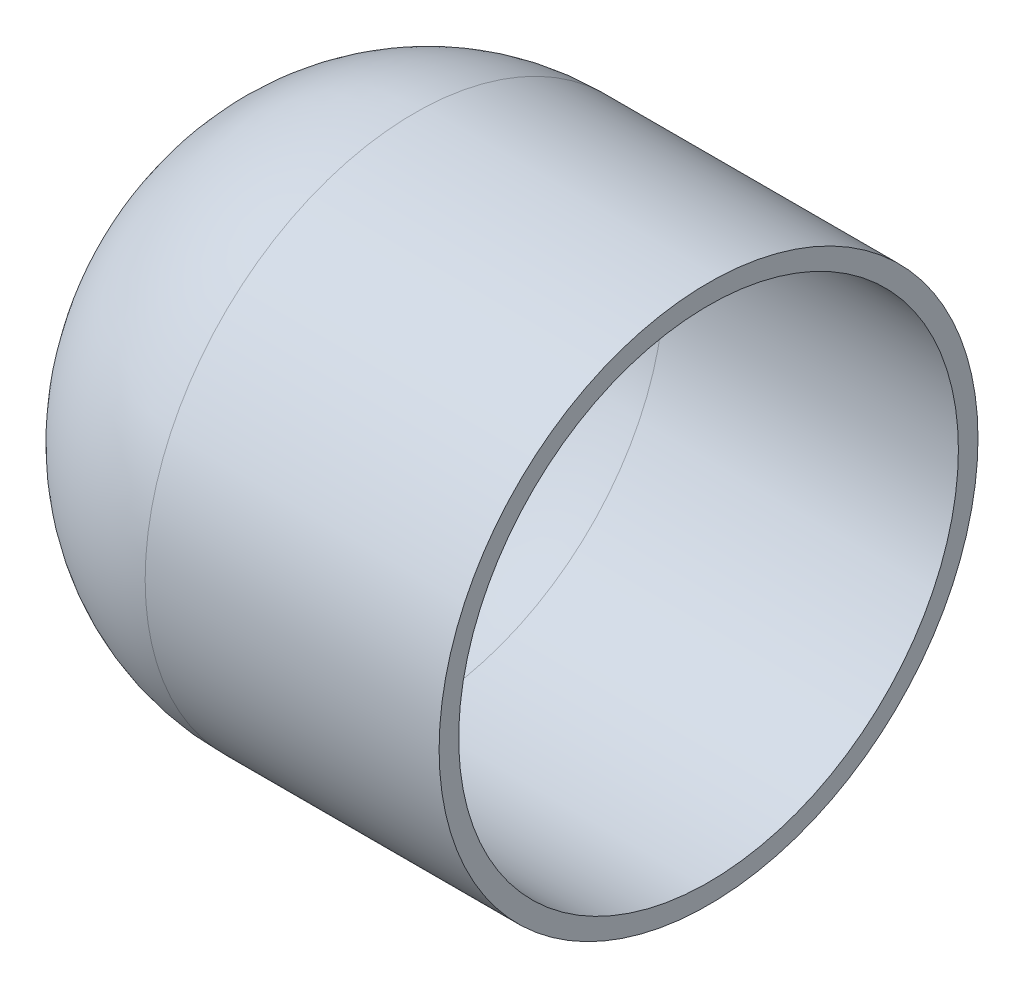
SolidWorks part; units mm, degrees
ref_plane "Ön Düzlem" through (0, 0, 0) normal (0, 0, 1) x (1, 0, 0)
ref_plane "Üst Düzlem" through (0, 0, 0) normal (0, 1, 0) x (1, 0, 0)
ref_plane "Sağ Düzlem" through (0, 0, 0) normal (1, 0, 0) x (0, 0, -1)
sketch "Çizim2" plane through (0, 0, 0) normal (0, 0, 1) x (1, 0, 0)
  line L0 (0, 0) -> (0, 27.5) construction
  line L1 (0, 0) -> (-101.4286, 0) construction
  line L2 (0, 27.5) -> (-30, 27.5)
  line L4 (0, 25.5) -> (-30, 25.5)
  line L6 (-50.8, 13.8) -> (-50.8, 15.8)
  line L7 (-50.8, 15.8) -> (-50.8, 13.8)
  line L8 (0, 27.5) -> (0, 25.5)
  arc A0 (-50.8, 13.8) -> (-30, 25.5) centre (-30.9763, 2.8967) cw
  arc A1 (-30, 27.5) -> (-50.8, 15.8) centre (-30.192, 3.5025) ccw
  dimension "D8" = 23.9982
  dimension "D9" = 22.6244
  dimension "D1" = 30
  dimension "D2" = 27.5
  dimension "D3" = 50.8
  dimension "D4" = 2
  dimension "D5" = 2
  dimension "D6" = 15.8
  dimension "D7" = 30
revolve "Döndür2" add sketch "Çizim2" angle 360 about L1
